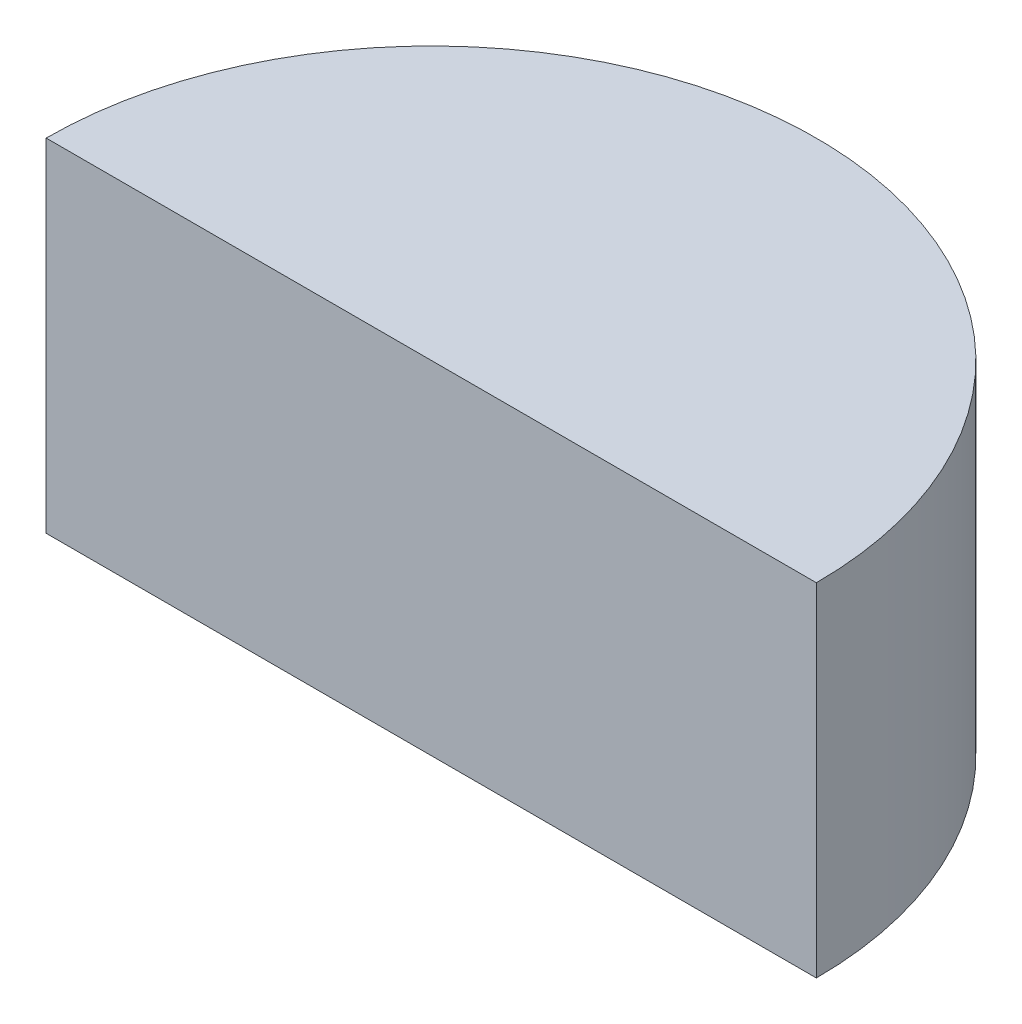
SolidWorks part; units mm, degrees
material "刚性聚氨酯泡沫体"
ref_plane "前视基准面" through (0, 0, 0) normal (0, 0, 1) x (1, 0, 0)
ref_plane "上视基准面" through (0, 0, 0) normal (0, 1, 0) x (1, 0, 0)
ref_plane "右视基准面" through (0, 0, 0) normal (1, 0, 0) x (0, 0, -1)
other "Configuration Table"
other "聚氨酯"
sketch "草图1" plane through (0, 0, 0) normal (0, 1, 0) x (1, 0, 0)
  line L2 (-2.25, 0) -> (2.25, 0)
  arc A1 (2.25, 0) -> (-2.25, 0) centre (0, 0) ccw
  dimension "D2" = 4.5
extrude "凸台-拉伸1" add sketch "草图1" along normal blind 2
